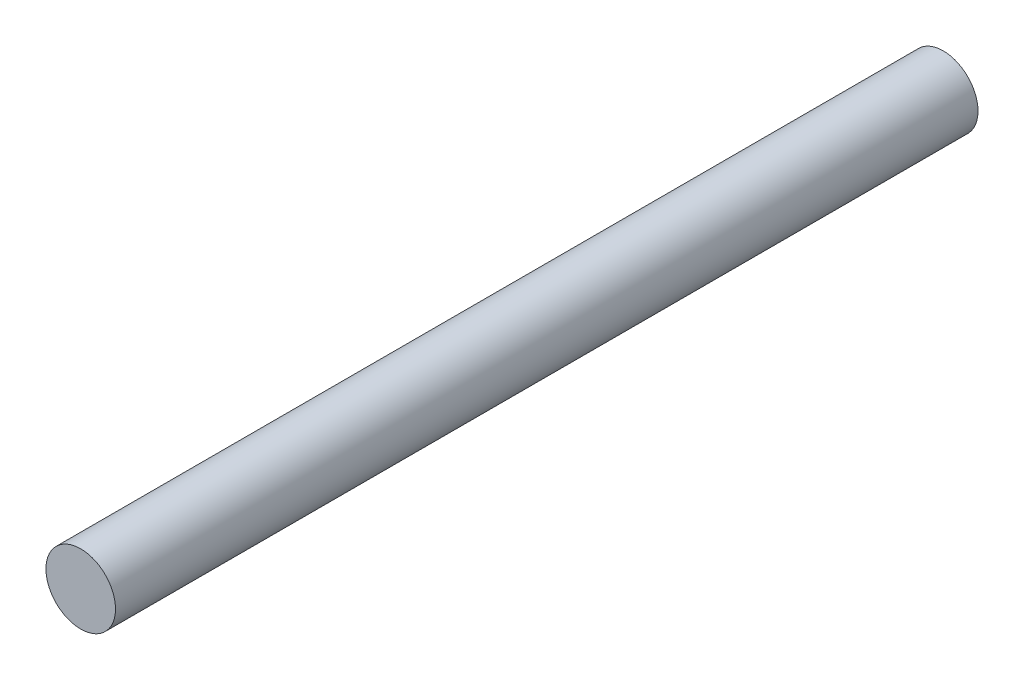
SolidWorks part; units mm, degrees
ref_plane "Plan de face" through (0, 0, 0) normal (0, 0, 1) x (1, 0, 0)
ref_plane "Plan de dessus" through (0, 0, 0) normal (0, 1, 0) x (1, 0, 0)
ref_plane "Plan de droite" through (0, 0, 0) normal (1, 0, 0) x (0, 0, -1)
sketch "Esquisse1" plane through (0, 0, 0) normal (0, 0, 1) x (1, 0, 0)
  circle A0 centre (0, 0) radius 12.5
  dimension "D1" = 25
extrude "Boss.-Extru.1" add sketch "Esquisse1" along normal blind 310
